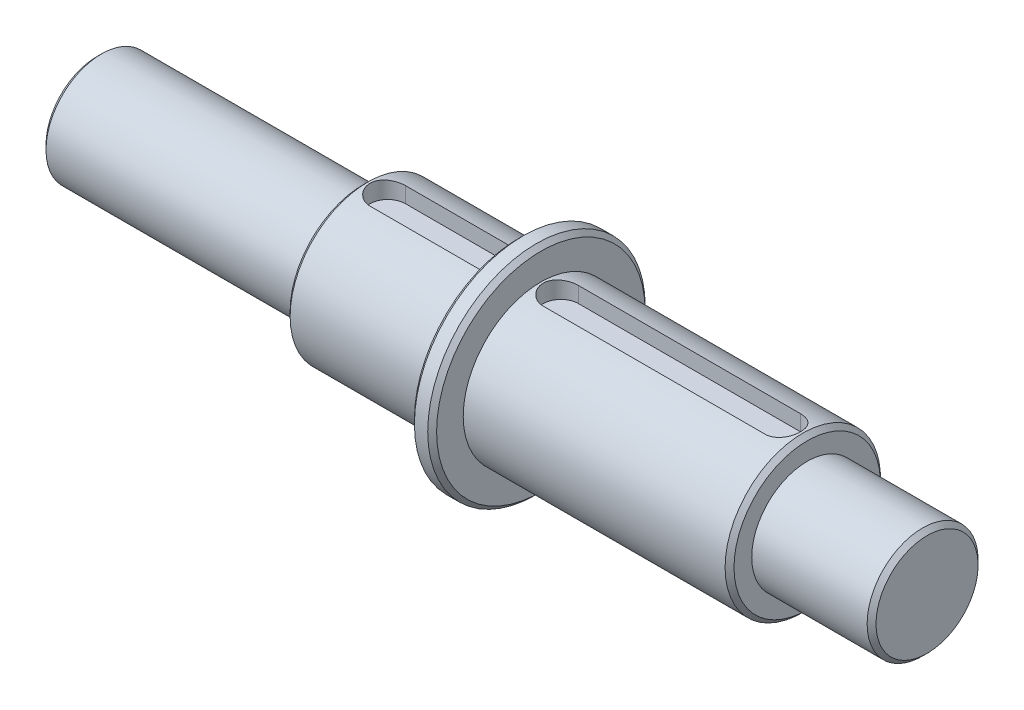
SolidWorks part; units mm, degrees
ref_plane "Front Plane" through (0, 0, 0) normal (0, 0, 1) x (1, 0, 0)
ref_plane "Top Plane" through (0, 0, 0) normal (0, 1, 0) x (1, 0, 0)
ref_plane "Right Plane" through (0, 0, 0) normal (1, 0, 0) x (0, 0, -1)
sketch "Sketch1" plane through (0, 0, 0) normal (0, 0, 1) x (1, 0, 0)
  line L0 (-126.1902, 0) -> (140.8959, 0) construction
  line L1 (-94.1955, 0) -> (-94.1955, 11.5)
  line L2 (-93.1955, 12.5) -> (-34.1955, 12.5)
  line L3 (92.8045, 11.5) -> (92.8045, 0)
  line L4 (-34.1955, 12.5) -> (-34.1955, 16.5)
  line L5 (-33.1955, 17.5) -> (0.8045, 17.5)
  line L6 (0.8045, 17.5) -> (0.8045, 23.5)
  line L7 (1.8045, 24.5) -> (4.8045, 24.5)
  line L8 (5.8045, 23.5) -> (5.8045, 17.5)
  line L9 (5.8045, 17.5) -> (64.8045, 17.5)
  line L10 (65.8045, 16.5) -> (65.8045, 12.5)
  line L11 (65.8045, 12.5) -> (91.8045, 12.5)
  line L12 (-94.1955, 11.5) -> (-93.1955, 12.5)
  line L13 (-34.1955, 16.5) -> (-33.1955, 17.5)
  line L14 (0.8045, 23.5) -> (1.8045, 24.5)
  line L15 (4.8045, 24.5) -> (5.8045, 23.5)
  line L16 (64.8045, 17.5) -> (65.8045, 16.5)
  line L17 (91.8045, 12.5) -> (92.8045, 11.5)
  line L18 (-94.1955, 0) -> (92.8045, 0)
  point P4 (-94.1955, 12.5)
  point P5 (-16.6955, 12.5)
  point P6 (92.8045, 12.5)
  point P8 (35.8045, 12.5)
  point P9 (0.8045, 12.5)
  point P10 (-34.1955, 12.5)
  point P11 (5.8045, 12.5)
  point P12 (65.8045, 12.5)
  point P13 (-77.1955, 12.5)
  point P14 (75.8045, 12.5)
  point P16 (-34.1955, 17.5)
  point P19 (0.8045, 24.5)
  point P20 (5.8045, 24.5)
  point P22 (65.8045, 17.5)
  dimension "D1" = 187
  dimension "D2" = 12.5
  dimension "D3" = 95
  dimension "D4" = 130
  dimension "D5" = 17.5
  dimension "D6" = 17.5
  dimension "D7" = 100
  dimension "D8" = 30
  dimension "D9" = 17
  dimension "D10" = 17
  dimension "D11" = 5
  dimension "D12" = 7
  dimension "D13" = 5
revolve "Revolve1" add sketch "Sketch1" angle 360 about L0
ref_plane "Plane1" through (0, 17.5, 0) normal (0, 1, 0) x (1, 0, 0)
sketch "Sketch2" plane through (0, 17.5, 0) normal (0, 1, 0) x (1, 0, 0)
  line L3 (-28.6955, 0) -> (-3.6955, 0) construction
  line L4 (-28.6955, 4) -> (-3.6955, 4)
  line L5 (-28.6955, -4) -> (-3.6955, -4)
  arc A0 (-28.6955, 4) -> (-28.6955, -4) centre (-28.6955, 0) ccw
  arc A1 (-3.6955, -4) -> (-3.6955, 4) centre (-3.6955, 0) ccw
  point P8 (-16.1955, 0)
  dimension "D1" = 25
  dimension "D2" = 8
extrude "Cut-Extrude1" cut sketch "Sketch2" against normal blind 4
sketch "Sketch3" plane through (0, 17.5, 0) normal (0, 1, 0) x (1, 0, 0)
  line L3 (10.3045, 0) -> (60.3045, 0) construction
  line L4 (10.3045, 4) -> (60.3045, 4)
  line L5 (10.3045, -4) -> (60.3045, -4)
  arc A0 (10.3045, 4) -> (10.3045, -4) centre (10.3045, 0) ccw
  arc A1 (60.3045, -4) -> (60.3045, 4) centre (60.3045, 0) ccw
  point P8 (35.3045, 0)
  point P15 (22.4218, 0)
  dimension "D1" = 50
  dimension "D3" = 8
extrude "Cut-Extrude2" cut sketch "Sketch3" against normal blind 4
